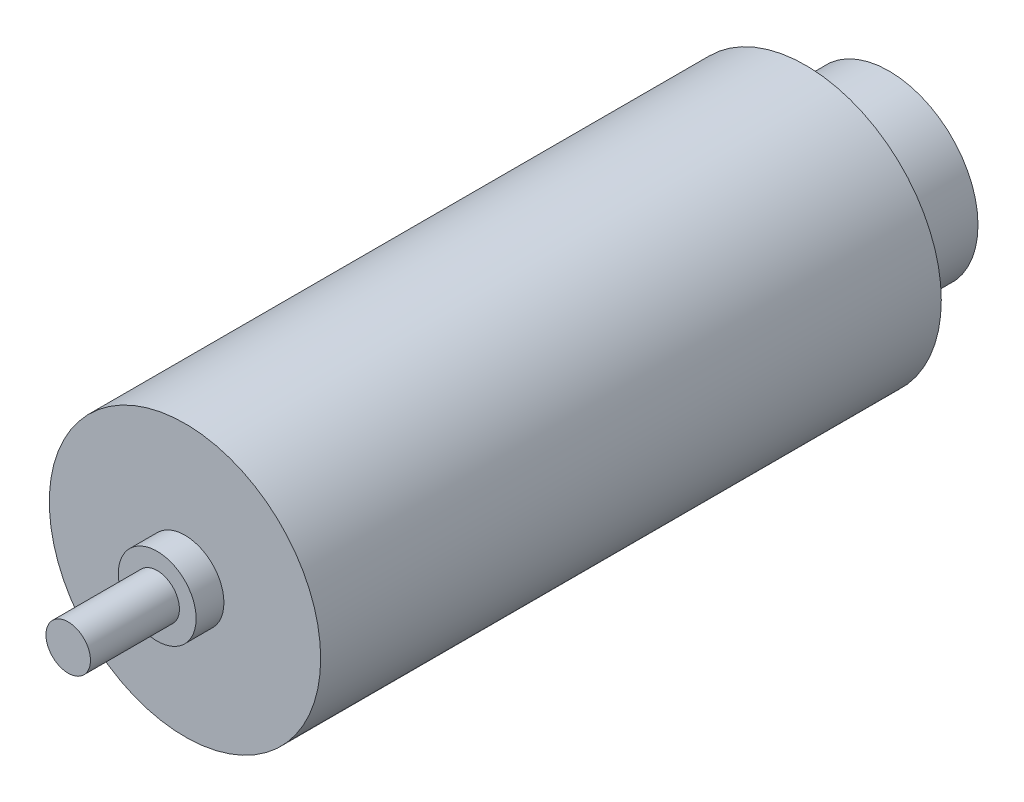
SolidWorks part; units mm, degrees
ref_plane "Front Plane" through (0, 0, 0) normal (0, 0, 1) x (1, 0, 0)
ref_plane "Top Plane" through (0, 0, 0) normal (0, 1, 0) x (1, 0, 0)
ref_plane "Right Plane" through (0, 0, 0) normal (1, 0, 0) x (0, 0, -1)
sketch "Sketch1" plane through (0, 0, 0) normal (0, 0, 1) x (1, 0, 0)
  circle A0 centre (0, 0) radius 12.2
  dimension "D1" = 24.4
extrude "Boss-Extrude1" add sketch "Sketch1" along normal blind 55.8
sketch "Sketch2" plane through (0, 0, 0) normal (0, 0, -1) x (-1, 0, 0)
  circle A0 centre (0, 0) radius 8
  dimension "D1" = 16
extrude "Boss-Extrude2" add sketch "Sketch2" along normal blind 7.5
sketch "Sketch3" plane through (0, 0, 55.8) normal (0, 0, 1) x (1, 0, 0)
  circle A0 centre (0, 0) radius 3.5
  dimension "D1" = 7
extrude "Boss-Extrude3" add sketch "Sketch3" along normal blind 2.5
sketch "Sketch4" plane through (0, 0, 58.3) normal (0, 0, 1) x (1, 0, 0)
  circle A0 centre (0, 0) radius 2
  dimension "D1" = 4
extrude "Boss-Extrude4" add sketch "Sketch4" along normal blind 8
equation "\"D1@Boss-Extrude1\"=26.5+29.3"
